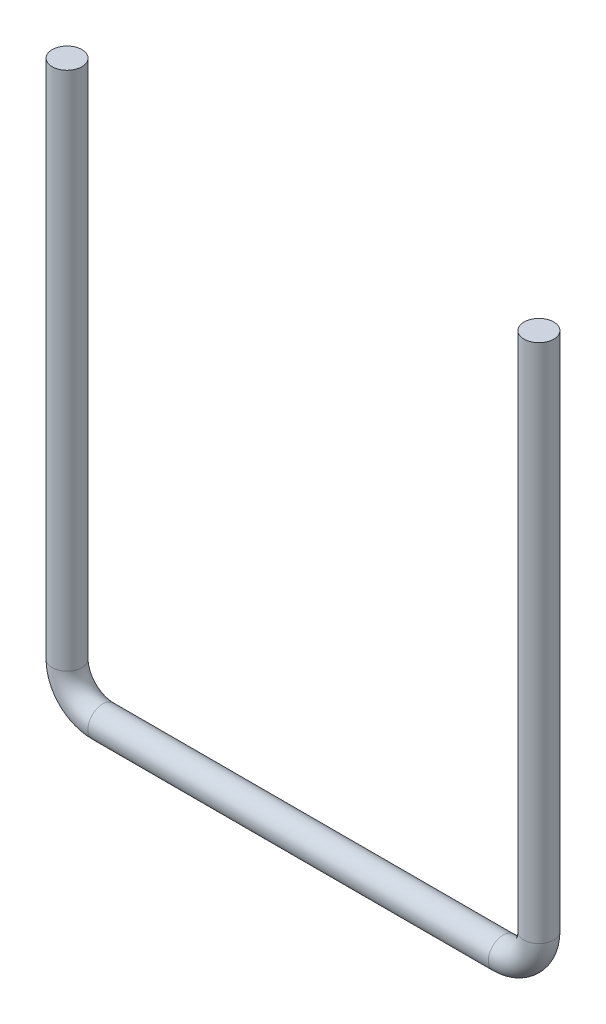
SolidWorks part; units mm, degrees
ref_plane "Front Plane" through (0, 0, 0) normal (0, 0, 1) x (1, 0, 0)
ref_plane "Top Plane" through (0, 0, 0) normal (0, 1, 0) x (1, 0, 0)
ref_plane "Right Plane" through (0, 0, 0) normal (1, 0, 0) x (0, 0, -1)
sketch "Sketch6" plane through (0, 0, 0) normal (0, 0, 1) x (1, 0, 0)
  line L0 (0, 0) -> (0, -36.4)
  line L1 (2.5, -38.9) -> (30.5, -38.9)
  line L2 (33, -36.4) -> (33, 0)
  arc A0 (0, -36.4) -> (2.5, -38.9) centre (2.5, -36.4) ccw
  arc A1 (30.5, -38.9) -> (33, -36.4) centre (30.5, -36.4) ccw
  dimension "D1" = 2.5
  dimension "D2" = 2.5
  dimension "D3" = 36.4
  dimension "D4" = 28
sketch "Sketch7" plane through (0, 0, 0) normal (0, 1, 0) x (1, 0, 0)
  circle A0 centre (0, 0) radius 1.04
  dimension "D1" = 2.08
sweep "Sweep2" add profiles "Sketch7" path "Sketch6"
